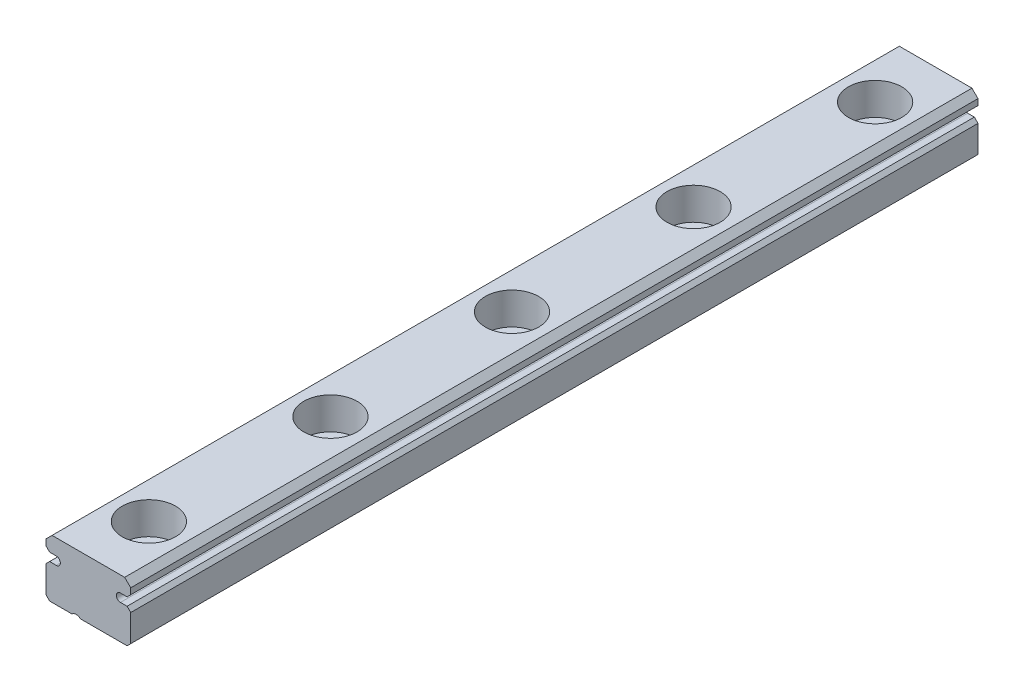
SolidWorks part; units mm, degrees
ref_plane "Front Plane" through (0, 0, 0) normal (0, 0, 1) x (1, 0, 0)
ref_plane "Top Plane" through (0, 0, 0) normal (0, 1, 0) x (1, 0, 0)
ref_plane "Right Plane" through (0, 0, 0) normal (1, 0, 0) x (0, 0, -1)
sketch "Sketch3" plane through (0, 0, 0) normal (0, 0, 1) x (1, 0, 0)
  line L0 (-3.5, 0) -> (-1.35, 0)
  line L1 (0, 0) -> (0, 4.8) construction
  line L2 (-3.5, 4.8) -> (3.5, 4.8)
  line L3 (-3.5, 0) -> (-3.5, 2.83)
  line L4 (3.5, 4.8) -> (3.5, 3.5)
  line L5 (-3.5, 3.5) -> (-2.65, 3.5)
  line L6 (-2.65, 3.5) -> (-2.65, 2.83) construction
  line L7 (-2.65, 2.83) -> (-3.5, 2.83)
  line L8 (-3.5, 3.5) -> (-3.5, 4.8)
  line L9 (2.65, 3.5) -> (2.65, 2.83) construction
  line L10 (2.65, 2.83) -> (3.5, 2.83)
  line L11 (3.5, 3.5) -> (2.65, 3.5)
  line L12 (3.5, 2.83) -> (3.5, 0)
  line L13 (-0.65, 0) -> (3.5, 0)
  arc A0 (-2.65, 3.5) -> (-2.65, 2.83) centre (-2.65, 3.165) cw
  arc A1 (2.65, 3.5) -> (2.65, 2.83) centre (2.65, 3.165) ccw
  arc A2 (-1.35, 0) -> (-0.65, 0) centre (-1, -0.3571) cw
  point P8 (0, 4.8)
  dimension "D8" = 0.5
  dimension "D1" = 7
  dimension "D2" = 4.8
  dimension "D3" = 1.3
  dimension "D4" = 2.65
  dimension "D5" = 0.67
  dimension "D6" = 1
  dimension "D7" = 0.7
extrude "Boss-Extrude1" add sketch "Sketch3" along normal mid plane 70
chamfer "Chamfer1" distance 0.5 angle 45 2 edges at (3.5, 4.8, 0) (-3.5, 4.8, 0)
chamfer "Chamfer2" distance 0.3 angle 45 6 edges at (3.5, 0, 0) (-3.5, 0, 0) (-3.5, 2.83, 0) (3.5, 2.83, 0) (3.5, 3.5, 0) (-3.5, 3.5, 0)
hole_wizard "CBORE for M2 SHCS1" positions "Sketch4" profile "Sketch5" counterbore size "M2" standard "ANSI Metric" end condition up to next
sketch "Sketch4" plane through (0, 4.8, 0) normal (0, 1, 0) x (1, 0, 0)
  line L0 (3, -35) -> (-3, -35) construction
  point P0 (0, -30)
  dimension "D1" = 5
sketch "Sketch5" plane through (0, 4.8, 30) normal (1, 0, 0) x (0, 0, 1)
  line L0 (0, 0) -> (0, 4.8)
  line L1 (0, 4.8) -> (1.2, 4.8)
  line L3 (1.2, 4.8) -> (1.2, 2.65)
  line L4 (1.2, 2.65) -> (2.2, 2.65)
  line L5 (2.2, 2.65) -> (2.2, 0)
  line L7 (2.2, 0) -> (0, 0)
  line L11 (0, -6.35) -> (0, 107.95) construction
  dimension "Thru Hole Dia." = 2.4
  dimension "Thru Hole Depth" = 4.8
  dimension "C'Bore Dia." = 4.4
  dimension "C'Bore Depth" = 2.65
pattern_linear "LPattern1" count 5 spacing 15 along (0, 0, -1) of "CBORE for M2 SHCS1"
